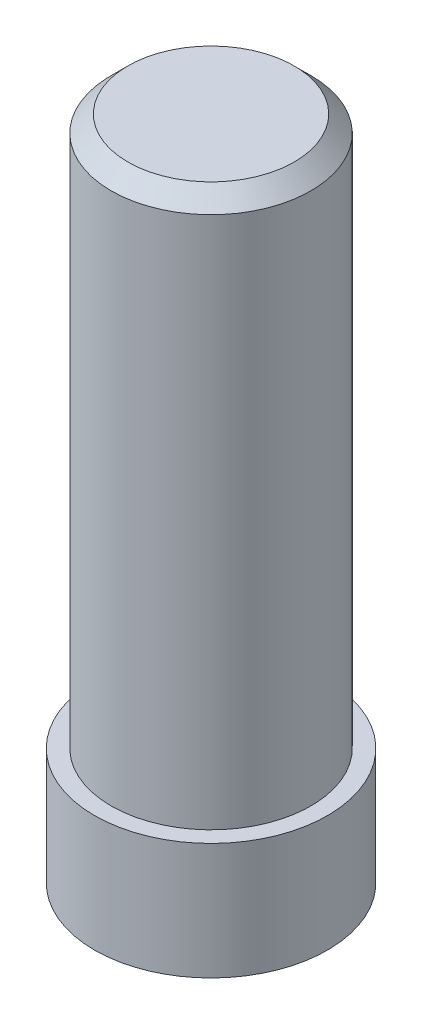
SolidWorks part; units mm, degrees
ref_plane "前视基准面" through (0, 0, 0) normal (0, 0, 1) x (1, 0, 0)
ref_plane "上视基准面" through (0, 0, 0) normal (0, 1, 0) x (1, 0, 0)
ref_plane "右视基准面" through (0, 0, 0) normal (1, 0, 0) x (0, 0, -1)
other "Configuration Table"
sketch "草图1" plane through (0, 0, 0) normal (0, 1, 0) x (1, 0, 0)
  circle A0 centre (0, 0) radius 7
  dimension "D1" = 14
extrude "凸台-拉伸1" add sketch "草图1" along normal blind 7
sketch "草图2" plane through (0, 0, 0) normal (0, 1, 0) x (1, 0, 0)
  circle A0 centre (0, 0) radius 6
  dimension "D1" = 12
extrude "凸台-拉伸2" add sketch "草图2" along normal blind 33 from surface at 7 starting at face at (0, 7, 7)
sketch "草图3" plane through (0, 0, 0) normal (0, 0, 1) x (1, 0, 0)
  line L0 (6, 40) -> (5, 40)
  line L1 (6, 40) -> (-6, 40) construction
  line L2 (5, 40) -> (6, 39)
  line L3 (6, 39) -> (6, 40)
  dimension "D1" = 1
  dimension "D2" = 1
revolve "切除-旋转1" cut sketch "草图3" angle 360 about axis through (0, 40, 0) along (0, -1, 0)
